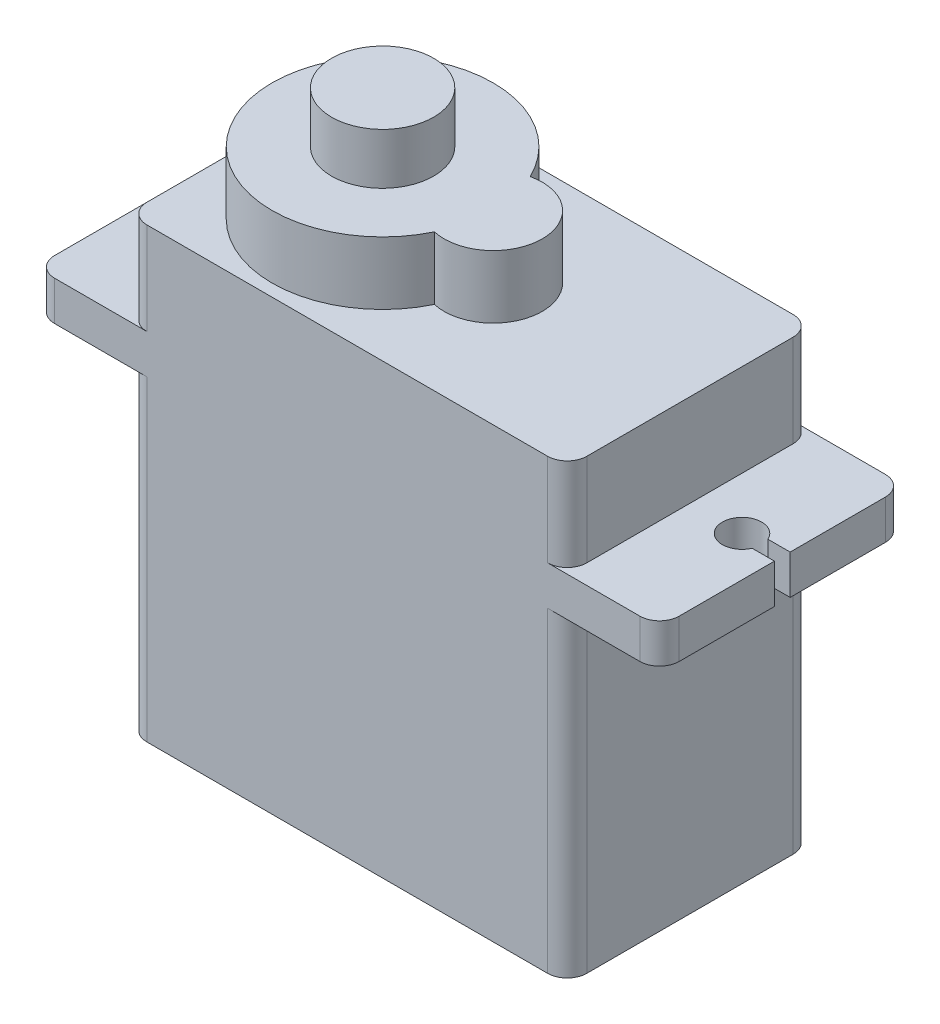
SolidWorks part; units mm, degrees
ref_plane "Front Plane" through (0, 0, 0) normal (0, 0, 1) x (1, 0, 0)
ref_plane "Top Plane" through (0, 0, 0) normal (0, 1, 0) x (1, 0, 0)
ref_plane "Right Plane" through (0, 0, 0) normal (1, 0, 0) x (0, 0, -1)
sketch "Sketch1" plane through (0, 0, 0) normal (0, 1, 0) x (1, 0, 0)
  line L1 (-11.2, 6.25) -> (11.2, 6.25)
  line L2 (-11.2, 6.25) -> (-11.2, -6.25)
  line L3 (-11.2, -6.25) -> (11.2, -6.25)
  line L4 (11.2, 6.25) -> (11.2, -6.25)
  line L5 (-11.2, 6.25) -> (11.2, -6.25) construction
  line L6 (-11.2, -6.25) -> (11.2, 6.25) construction
  point P0 (0, 0)
  dimension "D1" = 12.5
  dimension "D2" = 22.4
extrude "Boss-Extrude1" add sketch "Sketch1" along normal mid plane 22.8
sketch "Sketch2" plane through (0, 11.4, 0) normal (0, 1, 0) x (1, 0, 0)
  line L0 (-11.2, 6.25) -> (-11.2, -6.25) construction
  circle A0 centre (-4.45, 0) radius 5.63
  circle A1 centre (1.18, 0) radius 2.5
  point P6 (1.18, 0)
  dimension "D2" = 11.26
  dimension "D3" = 5
  dimension "D1" = 6.75
extrude "Boss-Extrude2" add sketch "Sketch2" along normal blind 3.2 contours A0 A1 | A0 A1 | A1 A0
sketch "Sketch3" plane through (0, 0, 0) normal (0, 0, 1) x (1, 0, 0)
  line L0 (-11.2, 11.4) -> (11.2, 11.4) construction
  line L1 (-15.9, 6.7) -> (15.9, 6.7)
  line L2 (-15.9, 6.7) -> (-15.9, 4.7)
  line L3 (-15.9, 4.7) -> (15.9, 4.7)
  line L4 (15.9, 6.7) -> (15.9, 4.7)
  line L5 (-11.2, 11.4) -> (-11.2, -11.4) construction
  line L6 (11.2, 11.4) -> (11.2, -11.4) construction
  dimension "D1" = 4.7
  dimension "D2" = 2
  dimension "D3" = 4.7
  dimension "D4" = 4.7
extrude "Boss-Extrude3" add sketch "Sketch3" along normal through all and the other way through all
sketch "Sketch4" plane through (0, 6.7, 0) normal (0, 1, 0) x (1, 0, 0)
  line L0 (-15.9, -6.25) -> (-15.9, 6.25) construction
  line L1 (15.9, -6.25) -> (15.9, 6.25) construction
  circle A0 centre (-13.85, 0) radius 1
  circle A1 centre (13.85, 0) radius 1
  point P6 (-13.85, 0)
  point P7 (-13.85, 0)
  point P8 (0, 0)
  point P9 (0, 0)
  dimension "D2" = 2
  dimension "D1" = 2.05
  dimension "D3" = 2.05
extrude "Cut-Extrude1" cut sketch "Sketch4" against normal through all
sketch "Sketch5" plane through (0, 6.7, 0) normal (0, 1, 0) x (1, 0, 0)
  line L0 (-17.95, 0) -> (-13.85, 0) construction
  line L1 (-15.9, -6.25) -> (-15.9, 6.25) construction
  line L2 (-17.95, 0.4) -> (-13.85, 0.4)
  line L3 (-17.95, -0.4) -> (-13.85, -0.4)
  line L4 (17.95, 0) -> (13.85, 0) construction
  line L5 (15.9, -6.25) -> (15.9, 6.25) construction
  line L6 (17.95, -0.4) -> (13.85, -0.4)
  line L7 (17.95, 0.4) -> (13.85, 0.4)
  arc A0 (-17.95, 0.4) -> (-17.95, -0.4) centre (-17.95, 0) ccw
  arc A1 (-13.85, -0.4) -> (-13.85, 0.4) centre (-13.85, 0) ccw
  arc A2 (17.95, -0.4) -> (17.95, 0.4) centre (17.95, 0) ccw
  arc A3 (13.85, 0.4) -> (13.85, -0.4) centre (13.85, 0) ccw
  point P5 (-15.9, 0)
  point P15 (15.9, 0)
  dimension "D1" = 0.8
  dimension "D2" = 0.8
extrude "Cut-Extrude2" cut sketch "Sketch5" against normal through all
sketch "Sketch6" plane through (0, 14.6, 0) normal (0, 1, 0) x (1, 0, 0)
  circle A0 centre (-4.45, 0) radius 2.6
  dimension "D1" = 5.2
extrude "Boss-Extrude4" add sketch "Sketch6" along normal blind 2.6
fillet "Fillet1" radius 1 12 edges at (11.2, 9.05, -6.25) (11.2, -3.35, -6.25) (11.2, -3.35, 6.25) (11.2, 9.05, 6.25) (-11.2, 9.05, -6.25) (-11.2, -3.35, -6.25) (-11.2, -3.35, 6.25) (-11.2, 9.05, 6.25) (-15.9, 5.7, 6.25) (-15.9, 5.7, -6.25) (15.9, 5.7, -6.25) (15.9, 5.7, 6.25)
sketch "Sketch7" plane through (-11.2, 0, 0) normal (-1, 0, 0) x (0, 0, 1)
  line L0 (-5.25, -11.4) -> (5.25, -11.4) construction
  arc A0 (0.25, -6.967) -> (-0.25, -6.967) centre (0, -7.4) ccw
  arc A1 (0.25, -7.833) -> (0.25, -6.967) centre (0.5, -7.4) ccw
  arc A2 (-0.25, -6.967) -> (-0.25, -7.833) centre (-0.5, -7.4) ccw
  arc A3 (-0.25, -7.833) -> (0.25, -7.833) centre (0, -7.4) ccw
  point P9 (0, 0)
  point P11 (0, 0)
  dimension "D1" = 1
  dimension "D2" = 4
sketch "Sketch8" plane through (0, 0, 0) normal (0, 0, 1) x (1, 0, 0)
  line L0 (-11.2, -7.4) -> (-12.7, -7.4)
  line L1 (-11.2, -6.9) -> (-11.2, -7.9) construction
  arc A0 (-12.7, -7.4) -> (-14.7, -11.4) centre (-12.7, -9.9) ccw
  point P6 (-13.0747, -9.9)
  dimension "D1" = 2.5
  dimension "D2" = 1.5
  dimension "D3" = 4
sweep "Sweep1" add profiles "Sketch7" path "Sketch8"
